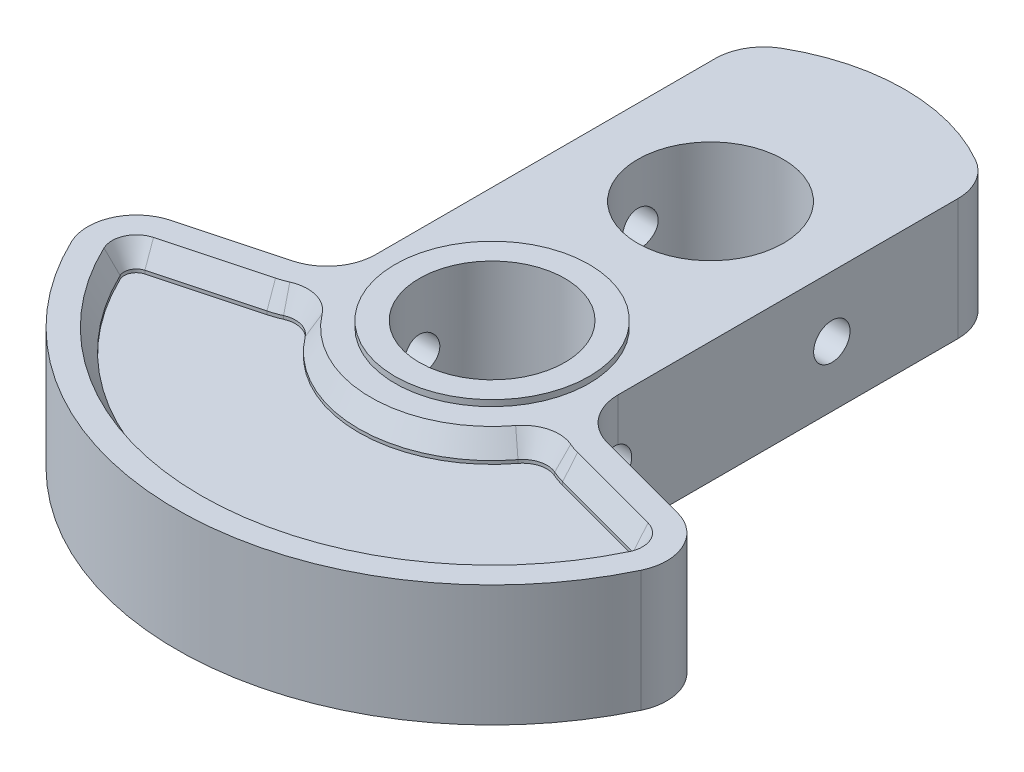
SolidWorks part; units mm, degrees
ref_plane "Front Plane" through (0, 0, 0) normal (0, 0, 1) x (1, 0, 0)
ref_plane "Top Plane" through (0, 0, 0) normal (0, 1, 0) x (1, 0, 0)
ref_plane "Right Plane" through (0, 0, 0) normal (1, 0, 0) x (0, 0, -1)
sketch "Sketch1" plane through (0, 0, 0) normal (0, 1, 0) x (1, 0, 0)
  line L0 (0, 0) -> (0, 47.7565) construction
  line L1 (10, 0) -> (10, 30.49)
  line L2 (-10, 0) -> (-10, 30.49)
  line L3 (-10, -2.6795) -> (-25.1141, -6.7293) construction
  line L4 (10, 0) -> (10, 47.7565) construction
  line L5 (-10, 0) -> (-10, 47.7565) construction
  line L6 (-25.1141, -6.7293) -> (-10, -2.6795) construction
  line L7 (10, -2.6795) -> (25.1141, -6.7293) construction
  line L8 (0, 0) -> (0, -46.0295) construction
  line L9 (-10, 0) -> (-10, -2.6795)
  line L10 (-10, -2.6795) -> (-25.1141, -6.7293)
  line L11 (10, 0) -> (10, -2.6795)
  line L12 (10, -2.6795) -> (25.1141, -6.7293)
  arc A1 (10, 30.49) -> (-10, 30.49) centre (0, 18) ccw
  arc A2 (25.1141, -6.7293) -> (-25.1141, -6.7293) centre (0, 0) cw
  dimension "D5" = 26
  dimension "D1" = 18
  dimension "D6" = 75
  dimension "D7" = 75
  dimension "D3" = 10
  dimension "D4" = 10
extrude "Boss-Extrude1" add sketch "Sketch1" along normal mid plane 10
fillet "Fillet1" radius 4 6 edges at (10, 0, -30.49) (-10, 0, -30.49) (10, 0, 2.6795) (-10, 0, 2.6795) (-25.1141, 0, 6.7293) (25.1141, 0, 6.7293)
sketch "Sketch2" plane through (0, 5, 0) normal (0, 1, 0) x (1, 0, 0)
  circle A0 centre (0, 0) radius 8
  dimension "D1" = 16
extrude "Boss-Extrude2" add sketch "Sketch2" along normal mid plane 1
sketch "Sketch3" plane through (0, -5, 0) normal (0, -1, 0) x (1, 0, 0)
  circle A0 centre (0, -18) radius 8
  dimension "D1" = 16
  dimension "D2" = 18
extrude "Boss-Extrude3" add sketch "Sketch3" along normal mid plane 1
sketch "Sketch4" plane through (0, 5.5, 0) normal (0, 1, 0) x (1, 0, 0)
  circle A0 centre (0, 0) radius 6
  circle A1 centre (0, 18) radius 6
  dimension "D1" = 12
  dimension "D2" = 12
extrude "Cut-Extrude1" cut sketch "Sketch4" against normal through all
sketch "Sketch5" plane through (0, -5, 0) normal (0, -1, 0) x (1, 0, 0)
  line L4 (20.1197, 8.4969) -> (12.1883, 6.3717)
  line L5 (-12.1883, 6.3717) -> (-20.1197, 8.4969)
  line L6 (20.1197, 8.4969) -> (12.1883, 6.3717)
  line L7 (-12.1883, 6.3717) -> (-20.1197, 8.4969)
  arc A2 (12.1883, 6.3717) -> (7, -0.3898) centre (14, -0.3898) ccw
  arc A3 (12.1883, 6.3717) -> (9.7202, 5.1495) centre (14, -0.3898) ccw
  arc A5 (-13, -0.3898) -> (-13.7412, 0.5761) centre (-14, -0.3898) ccw
  arc A6 (20.1197, 8.4969) -> (20.7637, 9.8929) centre (19.8609, 9.4628) ccw
  arc A7 (20.7637, 9.8929) -> (-20.7637, 9.8929) centre (0, 0) ccw
  arc A8 (-20.7637, 9.8929) -> (-20.1197, 8.4969) centre (-19.8609, 9.4628) ccw
  arc A9 (20.1197, 8.4969) -> (20.7637, 9.8929) centre (19.8609, 9.4628) ccw
  arc A10 (20.7637, 9.8929) -> (-20.7637, 9.8929) centre (0, 0) ccw
  arc A11 (-20.7637, 9.8929) -> (-20.1197, 8.4969) centre (-19.8609, 9.4628) ccw
  arc A12 (-13, -0.3898) -> (-13.7412, 0.5761) centre (-14, -0.3898) ccw
  arc A13 (9.7202, 5.1495) -> (-9.7202, 5.1495) centre (0, 0) ccw
  arc A15 (-9.7202, 5.1495) -> (-12.1883, 6.3717) centre (-14, -0.3898) ccw
  point P0 (0, 0)
  dimension "D5" = 22
  dimension "D1" = 3
  dimension "D2" = 3
  dimension "D3" = 3
extrude "Cut-Extrude2" cut sketch "Sketch5" against normal blind 2 contours A15 A13 A3 L6 A9 A10 A11 L7
fillet "Fillet3" radius 2 2 edges at (-9.7202, -4, 5.1495) (9.7202, -4, 5.1495)
chamfer "Chamfer1" distance 1 angle 60 10 edges at (0, -5, 11) (9.8646, -5, 5.9082) (-9.8646, -5, 5.9082) (11.6743, -5, 6.2125) (-11.6743, -5, 6.2125) (16.154, -5, 7.4343) (-16.154, -5, 7.4343) (20.7689, -5, 9.044) (-20.7689, -5, 9.044) (0, -5, 23)
mirror "Mirror9" about plane through (0, 0, 0) normal (0, 1, 0) of "Cut-Extrude2", "Fillet3", "Chamfer1"
sketch "Sketch7" plane through (0, 0, 0) normal (1, 0, 0) x (0, 0, -1)
  circle A0 centre (0, 0) radius 1.5
  circle A1 centre (18, 0) radius 1.5
  dimension "D2" = 3
  dimension "D3" = 3
  dimension "D1" = 18
extrude "Cut-Extrude3" cut sketch "Sketch7" against normal through all and the other way through all contours A1 | A0
